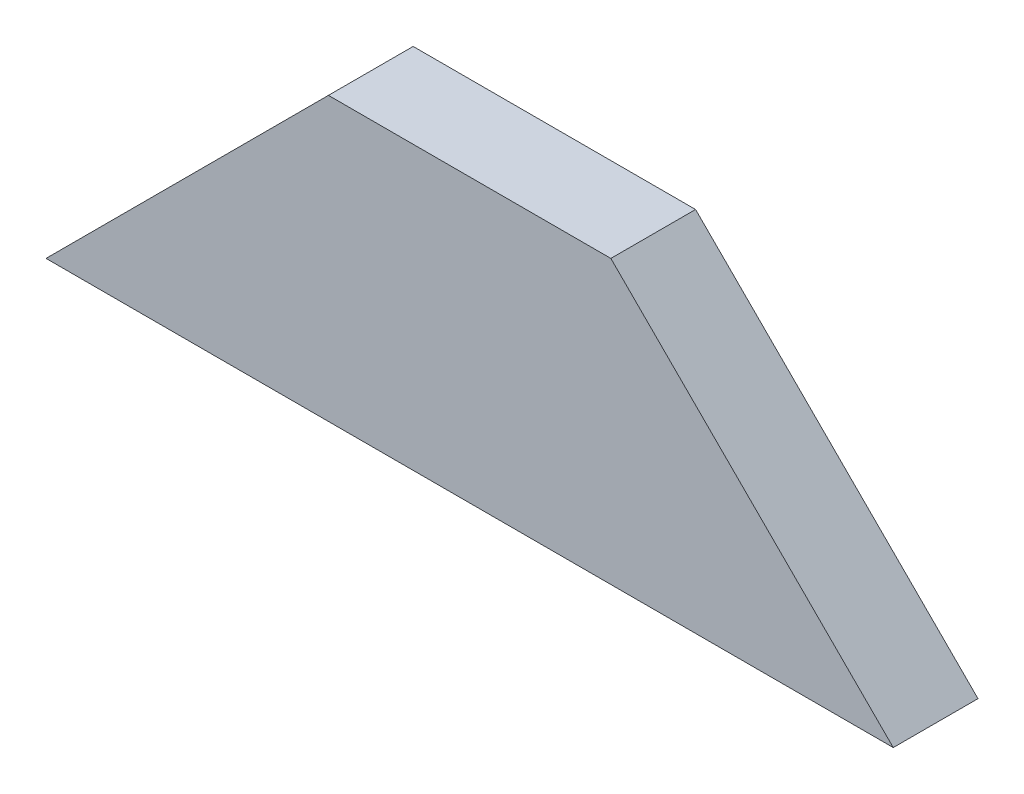
SolidWorks part; units mm, degrees
ref_plane "前视基准面" through (0, 0, 0) normal (0, 0, 1) x (1, 0, 0)
ref_plane "上视基准面" through (0, 0, 0) normal (0, 1, 0) x (1, 0, 0)
ref_plane "右视基准面" through (0, 0, 0) normal (1, 0, 0) x (0, 0, -1)
sketch "草图1" plane through (0, 0, 0) normal (0, 0, 1) x (1, 0, 0)
  line L0 (0, 0) -> (10, 10)
  line L1 (10, 10) -> (20, 10)
  line L2 (20, 10) -> (30, 0)
  line L3 (30, 0) -> (0, 0)
  line L6 (-3.0092, 3.0092) -> (0, 0) construction
  dimension "D1" = 10
  dimension "D2" = 30
  dimension "D3" = 225
extrude "凸台-拉伸1" add sketch "草图1" along normal blind 3
